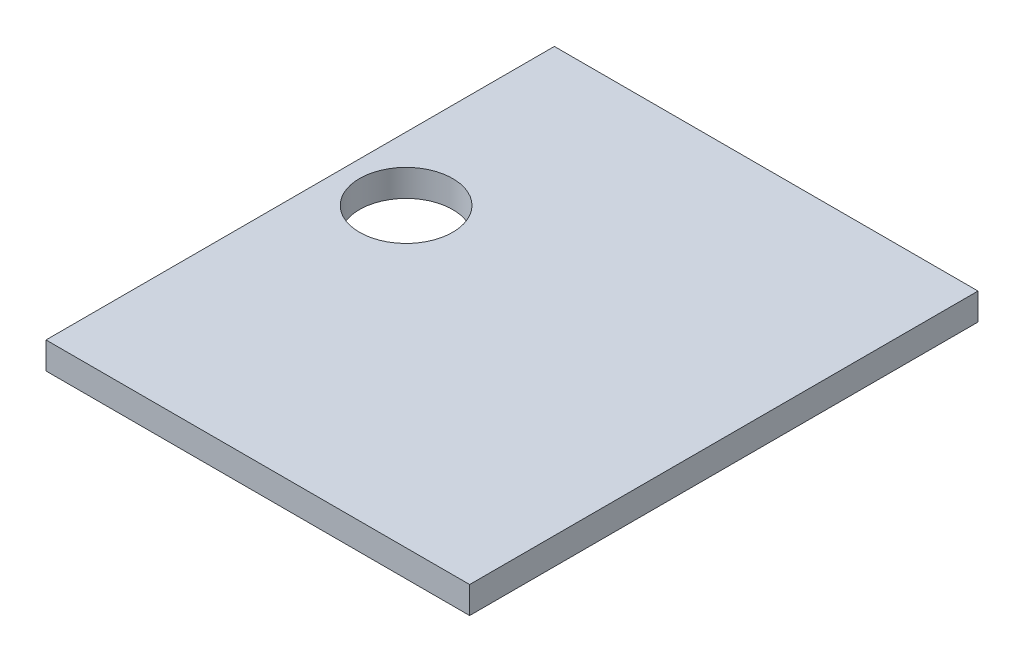
SolidWorks part; units mm, degrees
ref_plane "Front Plane" through (0, 0, 0) normal (0, 0, 1) x (1, 0, 0)
ref_plane "Top Plane" through (0, 0, 0) normal (0, 1, 0) x (1, 0, 0)
ref_plane "Right Plane" through (0, 0, 0) normal (1, 0, 0) x (0, 0, -1)
sketch "Sketch1" plane through (0, 0, 0) normal (0, 1, 0) x (1, 0, 0)
  line L1 (0, 0) -> (100, 0)
  line L2 (0, 0) -> (0, 120)
  line L3 (0, 120) -> (100, 120)
  line L4 (100, 0) -> (100, 120)
  line L5 (0, 0) -> (100, 120) construction
  line L6 (0, 120) -> (100, 0) construction
  circle A0 centre (15, 70) radius 11
  point P4 (50, 60)
  point P8 (0, 0)
  point P9 (0, 0)
  point P11 (0.2881, 120.7462)
  point P12 (60.7937, 127.2383)
  point P13 (-20.4105, 106.7629)
  dimension "D5" = 22
  dimension "D1" = 120
  dimension "D2" = 100
  dimension "D3" = 15
  dimension "D4" = 50
extrude "Boss-Extrude1" add sketch "Sketch1" along normal blind 6.35
